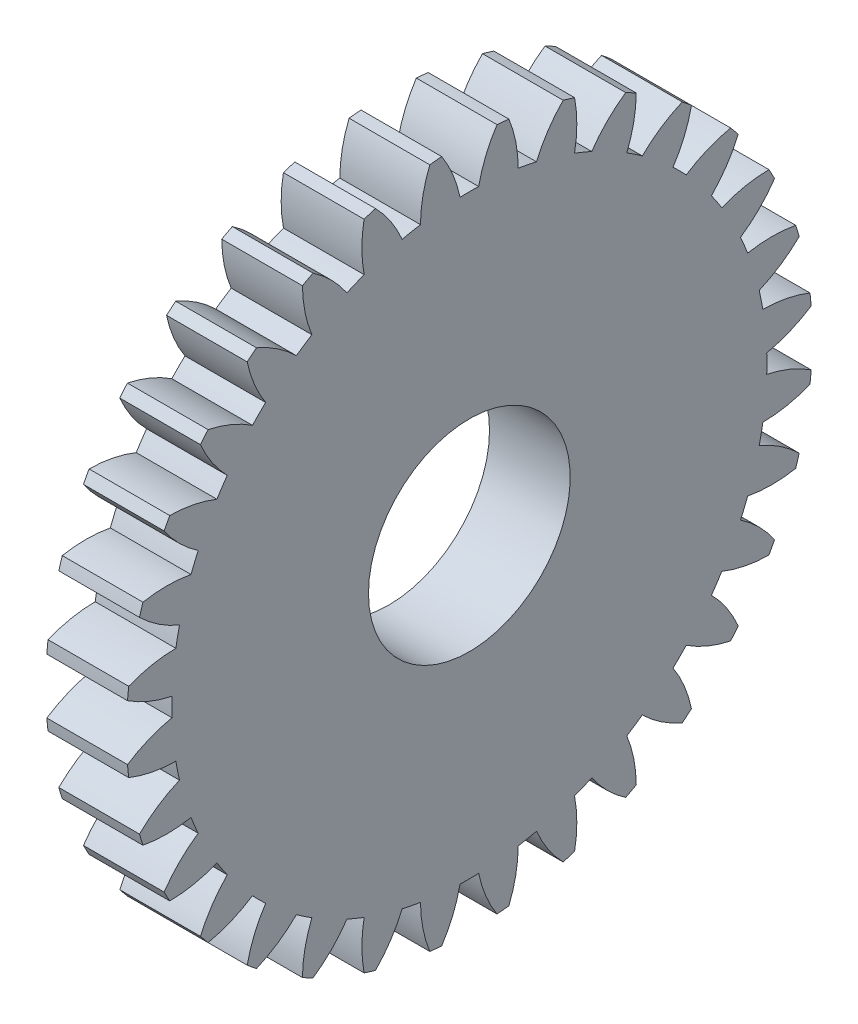
SolidWorks part; units mm, degrees
ref_plane "Plane1" through (0, 0, 0) normal (0, 0, 1) x (1, 0, 0)
ref_plane "Plane2" through (0, 0, 0) normal (0, 1, 0) x (1, 0, 0)
ref_plane "Plane3" through (0, 0, 0) normal (1, 0, 0) x (0, 0, -1)
sketch "HoldingSke" plane through (0, 0, 0) normal (0, 1, 0) x (1, 0, 0)
  line L0 (0, 0) -> (0.848, -0.5299)
  line L1 (-15, 0) -> (100, 0) construction
  line L2 (0, 0) -> (-2.1039, 2.3779)
  line L3 (0, 0) -> (-11.863, 4.5341)
  line L4 (0, 0) -> (7.3237, 4.5764)
  line L5 (0, 0) -> (-46.8476, -17.4728)
  line L6 (0, 0) -> (-3.3159, -2.2372)
  line L7 (-2.1039, 2.3779) -> (8.6586, 51.2059)
  line L8 (-76.2, 54.61) -> (-74.4, 54.61)
  line L9 (-71.009, 38.7566) -> (-53.1078, 45.2721)
  line L10 (-76.2, 71.12) -> (104.1128, 71.12)
  line L11 (0, 0) -> (-4, 0)
  line L12 (-76.2, 101.6) -> (-76.162, 101.6)
  line L13 (24.9733, 27.94) -> (52.9518, 28.4284)
  line L14 (24.9733, 27.94) -> (24.9743, 27.94)
  line L15 (24.9733, 27.94) -> (100.4006, 29.5858)
  line L16 (-63.627, -1) -> (-12.827, -1)
  circle A0 centre (0, 0) radius 5
  circle A1 centre (0, 0) radius 14.749
  circle A2 centre (0, 0) radius 37.5
  circle A3 centre (0, 0) radius 5
  dimension "MHD" = 29.498
  dimension "Hub_dia" = 75
  dimension "Bore" = 10
  dimension "MBD" = 10
  dimension "Num_teeth" = 32
  dimension "Pitch" = 1
  dimension "Overall_len" = 50
  dimension "Show_teeth" = 32
  dimension "Thickness" = 4
  dimension "OAL" = 50.0001
  dimension "T_dim" = 1.8
  dimension "Ap" = 20
  dimension "H" = 19.05
  dimension "Pitch_radius" = 180.3128
  dimension "Width" = 4
  dimension "Backlash" = 0.038
  dimension "Addendum_fac" = 1
  dimension "Dedendum_fac" = 1.25
  dimension "Clearance_fac" = 0.25
  dimension "Dedendum_add" = 0.001
  dimension "Module" = 1
sketch "BasProSke" plane through (0, 0, 0) normal (0, 1, 0) x (1, 0, 0)
  line L0 (-10, 0) -> (60, 0) construction
  line L1 (0, 0) -> (0, 17)
  line L2 (0, 0) -> (4, 0)
  line L3 (4, 0) -> (4, 17)
  line L4 (4, 17) -> (0, 17)
  dimension "Thickness" = 4
  dimension "Diameter" = 34
revolve "Base-Revolve" add sketch "BasProSke" angle 360 about L0
sketch "TooCutSke" plane through (0, 0, 0) normal (1, 0, 0) x (0, 0, -1)
  line L1 (0, 0) -> (0, 107) construction
  line L2 (0, 0) -> (-0.8516, 15.9773) construction
  line L3 (0, 0) -> (-3.1334, 31.8138) construction
  line L4 (-0.8516, 15.9773) -> (-1.5667, 15.9069) construction
  arc A0 (0.462, 14.7418) -> (-0.462, 14.7418) centre (0, 0) ccw
  arc A1 (1.3867, 16.9688) -> (-1.3867, 16.9688) centre (0, 0) ccw
  circle A2 centre (0, 0) radius 16 construction
  circle A3 centre (0, 0) radius 15.0351 construction
  arc A4 (-0.462, 14.7418) -> (-1.3867, 16.9688) centre (-6.7293, 13.4451) ccw
  arc A5 (1.3867, 16.9688) -> (0.462, 14.7418) centre (6.7293, 13.4451) ccw
  dimension "Root_dia" = 29.498
  dimension "Overcut_dia" = 34.0508
  dimension "Pitch_dia" = 32
  dimension "Base_dia" = 30.0702
  dimension "Flank_rad" = 6.4
  dimension "Half_ang" = 5.625
  dimension "Half_CT" = 0.7186
extrude "ToothCut" cut sketch "TooCutSke" along normal through all
fillet "Breaks" [suppressed] radius 0.02
fillet "RootFillets" [suppressed] radius 0.251
pattern_circular "TeethCuts" count 32 every 11.25 about axis through (-10, 0, 0) along (1, 0, 0) of "ToothCut", "RootFillets", "Breaks"
sketch "HubNeaOneSke" plane through (0, 0, 0) normal (-1, 0, 0) x (0, 0, 1)
  circle A0 centre (0, 0) radius 14.749
  dimension "Diameter" = 29.498
extrude "HubNearOne" [suppressed] add sketch "HubNeaOneSke" along normal blind 46.0001
sketch "HubNeaBotSke" plane through (0, 0, 0) normal (-1, 0, 0) x (0, 0, 1)
  circle A0 centre (0, 0) radius 14.749
  dimension "Diameter" = 29.498
extrude "HubNearBoth" [suppressed] add sketch "HubNeaBotSke" along normal blind 23
ref_plane "FarPln" through (4, 0, 0) normal (1, 0, 0) x (0, 0, -1)
sketch "HubFarSke" plane through (4, 0, 0) normal (1, 0, 0) x (0, 0, -1)
  circle A0 centre (0, 0) radius 14.749
  dimension "Diameter" = 29.498
extrude "HubFar" [suppressed] add sketch "HubFarSke" along normal blind 23
sketch "BorSke" plane through (0, 0, 0) normal (1, 0, 0) x (0, 0, -1)
  circle A0 centre (0, 0) radius 5
  dimension "Diameter" = 10
extrude "Bore" cut sketch "BorSke" along normal mid plane 100.0001
sketch "KeySke" plane through (0, 0, 0) normal (1, 0, 0) x (0, 0, -1)
  line L0 (-2, 0) -> (-2, 6.8)
  line L1 (-2, 6.8) -> (2, 6.8)
  line L2 (2, 6.8) -> (2, 0)
  line L3 (0, 0) -> (0, 34) construction
  line L4 (-2, 0) -> (2, 0)
  dimension "Width" = 4
  dimension "Offset" = 6.8
extrude "Keyway" [suppressed] cut sketch "KeySke" along normal mid plane 100.0001
pattern_circular "Keyway2" [suppressed] count 2 every 90 about axis through (-10, 0, 0) along (1, 0, 0)
sketch "Sketch1" plane through (4, 0, 0) normal (1, 0, 0) x (0, 0, -1)
  circle A0 centre (0, 0) radius 17
equation "' \"Module@HoldingSke\" = 6.35"
equation "' \"Num_teeth@HoldingSke\" = 12"
equation "' \"Ap@HoldingSke\" =  20"
equation "' \"Ap@HoldingSke\" = 20"
equation "' \"Width@HoldingSke\" = 0.5 * 25.4"
equation "' \"Hub_dia@HoldingSke\"= 1 * 25.4"
equation "' \"Hub_dia@HoldingSke\" = 1 * 25.4"
equation "' \"Overall_len@HoldingSke\" = 1.0 * 25.4"
equation "' \"Bore@HoldingSke\" = 0.75 * 25.4"
equation "' \"T_dim@HoldingSke\" = 0.1 * 25.4"
equation "' \"Width@KeySke\" = 0.25 * 25.4"
equation "' \"Show_teeth@HoldingSke\" = 13"
equation "' \"Backlash@HoldingSke\" = 0.009 * 25.4"
equation "' \"Addendum_fac@HoldingSke\" = 1.0"
equation "' \"Dedendum_fac@HoldingSke\" = 1.25"
equation "' \"Dedendum_add@HoldingSke\" = 0.00005 * 25.4"
equation "' \"Clearance_fac@HoldingSke\" = 0.25"
equation "\"Pitch@HoldingSke\" = 1 / \"Module@HoldingSke\""
equation "\"Overcut_dia@TooCutSke\" = (\"Num_teeth@HoldingSke\" + 2 * \"Addendum_fac@HoldingSke\") / \"Pitch@HoldingSke\" + 0.002 * 25.4"
equation "\"Pitch_dia@TooCutSke\" = \"Num_teeth@HoldingSke\" / \"Pitch@HoldingSke\""
equation "\"Base_dia@TooCutSke\" = \"Num_teeth@HoldingSke\" / \"Pitch@HoldingSke\" * cos((\"Ap@HoldingSke\"  * 3.14159265 / 180))"
equation "\"Root_dia@TooCutSke\" = (\"Num_teeth@HoldingSke\" + 2) / \"Pitch@HoldingSke\" - 2 * (\"Addendum_fac@HoldingSke\" + \"Dedendum_fac@HoldingSke\") / \"Pitch@HoldingSke\" - \"Dedendum_add@HoldingSke\" * 2"
equation "\"Half_ang@TooCutSke\" = 180 / \"Num_teeth@HoldingSke\""
equation "\"Half_CT@TooCutSke\" = \"Num_teeth@HoldingSke\" / \"Pitch@HoldingSke\" * sin((3.14159265 / 2 / \"Num_teeth@HoldingSke\")) / 2 - 7 * \"Backlash@HoldingSke\" / 4"
equation "\"Flank_rad@TooCutSke\" = \"Num_teeth@HoldingSke\" / \"Pitch@HoldingSke\" / 5"
equation "\"Radius@RootFillets\" = \"Clearance_fac@HoldingSke\" / \"Pitch@HoldingSke\" + \"Dedendum_add@HoldingSke\""
equation "\"Break_rad@Breaks\" = 0.02 / \"Pitch@HoldingSke\""
equation "\"Thickness@HoldingSke\" = \"Width@HoldingSke\""
equation "\"OAL@HoldingSke\" = \"Thickness@HoldingSke\""
equation "\"MHD@HoldingSke\" = (\"Num_teeth@HoldingSke\" + 2) / \"Pitch@HoldingSke\" - 2 * (\"Addendum_fac@HoldingSke\" + \"Dedendum_fac@HoldingSke\")  / \"Pitch@HoldingSke\" - \"Dedendum_add@HoldingSke\" * 2"
equation "\"MBD@HoldingSke\" = (\"Num_teeth@HoldingSke\" + 2) / \"Pitch@HoldingSke\" - 2 * (\"Addendum_fac@HoldingSke\" + \"Dedendum_fac@HoldingSke\")  / \"Pitch@HoldingSke\" - \"Dedendum_add@HoldingSke\" * 2 - 0.002 * 25.4"
equation "\"MHD@HoldingSke\" = ((sgn( \"MHD@HoldingSke\" - \"Hub_dia@HoldingSke\" )-1)*( \"MHD@HoldingSke\" - \"Hub_dia@HoldingSke\" ))/-2+ \"Hub_dia@HoldingSke\""
equation "\"MBD@HoldingSke\" = ((sgn( \"MBD@HoldingSke\" - \"Bore@HoldingSke\" )-1)*( \"MBD@HoldingSke\" - \"Bore@HoldingSke\" ))/-2+ \"Bore@HoldingSke\""
equation "\"OAL@HoldingSke\" = ((sgn( \"OAL@HoldingSke\" - \"Overall_len@HoldingSke\" )+1)*( \"OAL@HoldingSke\" - \"Overall_len@HoldingSke\" ))/2 + \"Overall_len@HoldingSke\" + 0.000002 * 25.4"
equation "\"Num_teeth@TeethCuts\" = int( \"Show_teeth@HoldingSke\" ) + 1"
equation "\"Num_teeth@TeethCuts\" = ((sgn( \"Num_teeth@TeethCuts\" - \"Num_teeth@HoldingSke\" )-1)*( \"Num_teeth@TeethCuts\" - \"Num_teeth@HoldingSke\" ))/-2+ \"Num_teeth@HoldingSke\""
equation "\"Num_teeth@TeethCuts\" = ((sgn( \"Num_teeth@TeethCuts\" - 2.0)+1)*( \"Num_teeth@TeethCuts\" - 2.0))/2 +2.0"
equation "\"Angle@TeethCuts\" = 360.0 / \"Num_teeth@HoldingSke\""
equation "\"Diameter@BasProSke\" = (\"Num_teeth@HoldingSke\" + 2 * \"Addendum_fac@HoldingSke\") / \"Pitch@HoldingSke\""
equation "\"Thickness@BasProSke\"  = \"Thickness@HoldingSke\""
equation "' \"Fillet_rad@BasProSke\" =  \"Thickness@HoldingSke\" * 0.05"
equation "' \"Fillet_rad@BasProSke\" = \"Thickness@HoldingSke\" * 0.05"
equation "\"MHD@HoldingSke\" = ((sgn( \"MHD@HoldingSke\" - \"Root_dia@TooCutSke\" )-1)*( \"MHD@HoldingSke\" - \"Root_dia@TooCutSke\" ))/-2+ \"Root_dia@TooCutSke\""
equation "\"Diameter@HubNeaOneSke\" = \"MHD@HoldingSke\""
equation "\"Length@HubNearOne\" = \"OAL@HoldingSke\" - \"Thickness@BasProSke\""
equation "\"Diameter@HubNeaBotSke\" = \"MHD@HoldingSke\""
equation "\"Length@HubNearBoth\" = ( \"OAL@HoldingSke\" - \"Thickness@BasProSke\" ) / 2.0"
equation "\"Thickness@FarPln\" = \"Thickness@BasProSke\""
equation "\"Diameter@HubFarSke\" = \"MHD@HoldingSke\""
equation "\"Length@HubFar\" = ( \"OAL@HoldingSke\" - \"Thickness@BasProSke\" ) / 2.0"
equation "\"Diameter@BorSke\" = \"MBD@HoldingSke\""
equation "\"D1@Bore\" = \"OAL@HoldingSke\" * 2.0"
equation "\"D1@Keyway\" = \"OAL@HoldingSke\" * 2.0"
equation "\"Offset@KeySke\" = \"T_dim@HoldingSke\" + \"MBD@HoldingSke\" / 2.0"
